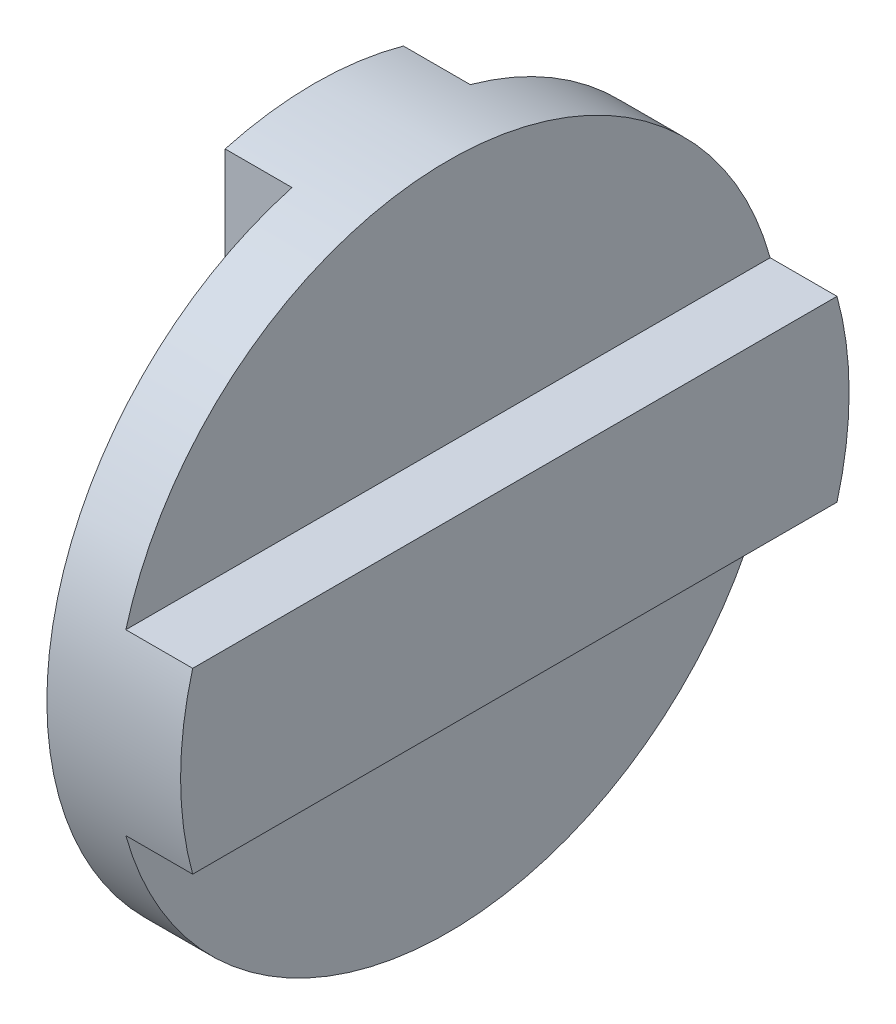
SolidWorks part; units mm, degrees
ref_plane "Front Plane" through (0, 0, 0) normal (0, 0, 1) x (1, 0, 0)
ref_plane "Top Plane" through (0, 0, 0) normal (0, 1, 0) x (1, 0, 0)
ref_plane "Right Plane" through (0, 0, 0) normal (1, 0, 0) x (0, 0, -1)
sketch "Sketch1" plane through (0, 0, 0) normal (1, 0, 0) x (0, 0, -1)
  circle A0 centre (0, 0) radius 75
  dimension "D1" = 150
extrude "Boss-Extrude1" add sketch "Sketch1" along normal blind 15
sketch "Sketch2" plane through (15, 0, 0) normal (1, 0, 0) x (0, 0, -1)
  line L1 (-72.2842, -20) -> (72.2842, -20)
  line L3 (-72.2842, 20) -> (72.2842, 20)
  circle A0 centre (0, 0) radius 75 construction
  arc A1 (-72.2842, 20) -> (-72.2842, -20) centre (0, 0) ccw
  arc A2 (72.2842, -20) -> (72.2842, 20) centre (0, 0) ccw
  dimension "D1" = 40
  dimension "D2" = 20
extrude "Boss-Extrude2" add sketch "Sketch2" along normal blind 15
sketch "Sketch3" plane through (0, 0, 0) normal (-1, 0, 0) x (0, 0, 1)
  line L2 (-20, 72.2842) -> (-20, -72.2842)
  line L4 (20, 72.2842) -> (20, -72.2842)
  circle A0 centre (0, 0) radius 75 construction
  arc A1 (-20, -72.2842) -> (20, -72.2842) centre (0, 0) ccw
  arc A2 (20, 72.2842) -> (-20, 72.2842) centre (0, 0) ccw
  dimension "D1" = 40
  dimension "D2" = 20
extrude "Boss-Extrude3" add sketch "Sketch3" along normal blind 15
